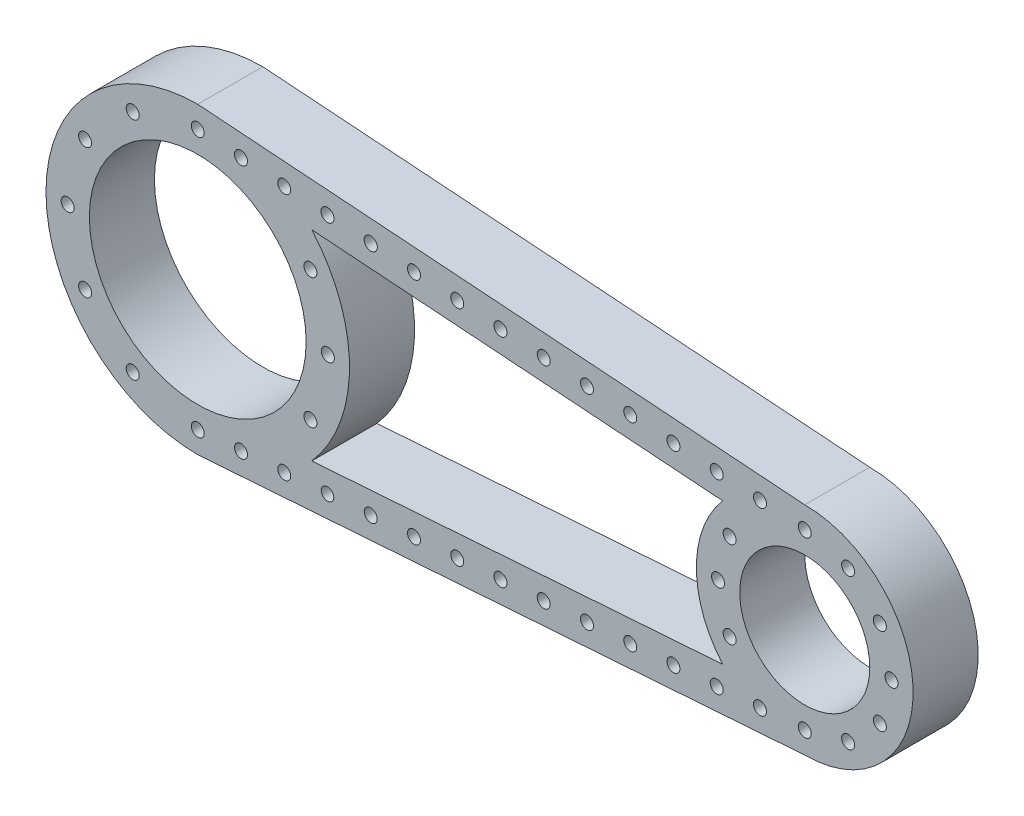
SolidWorks part; units mm, degrees
ref_plane "前视基准面" through (0, 0, 0) normal (0, 0, 1) x (1, 0, 0)
ref_plane "上视基准面" through (0, 0, 0) normal (0, 1, 0) x (1, 0, 0)
ref_plane "右视基准面" through (0, 0, 0) normal (1, 0, 0) x (0, 0, -1)
other "Configuration Table"
sketch "草图1" plane through (0, 0, 0) normal (0, 0, 1) x (1, 0, 0)
  line L0 (0, 0) -> (140, 0)
  line L1 (0, 35) -> (140, 25)
  line L2 (0, -35) -> (140, -25)
  circle A0 centre (0, 0) radius 35
  circle A1 centre (140, 0) radius 25
  dimension "D1" = 70
  dimension "D3" = 50
  dimension "D2" = 140
extrude "凸台-拉伸3" add sketch "草图1" along normal blind 5
sketch "草图4" plane through (0, 0, 5) normal (0, 0, 1) x (1, 0, 0)
  line L1 (-5, -5) -> (5, -5)
  line L2 (-5, -5) -> (-5, 5)
  line L3 (-5, 5) -> (5, 5)
  line L4 (5, -5) -> (5, 5)
  line L5 (-5, -5) -> (5, 5) construction
  line L6 (-5, 5) -> (5, -5) construction
  line L7 (135, -5) -> (145, -5)
  line L8 (135, -5) -> (135, 5)
  line L9 (135, 5) -> (145, 5)
  line L10 (145, -5) -> (145, 5)
  line L11 (135, -5) -> (145, 5) construction
  line L12 (135, 5) -> (145, -5) construction
  circle A0 centre (0, 0) radius 4
  circle A1 centre (-5, 5) radius 1.5
  circle A2 centre (5, 5) radius 1.5
  circle A3 centre (5, -5) radius 1.5
  circle A4 centre (-5, -5) radius 1.5
  circle A5 centre (140, 0) radius 4
  circle A6 centre (135, 5) radius 1.5
  circle A7 centre (145, 5) radius 1.5
  circle A8 centre (145, -5) radius 1.5
  circle A9 centre (135, -5) radius 1.5
  dimension "D1" = 8
  dimension "D4" = 3
  dimension "D6" = 8
  dimension "D9" = 3
  dimension "D2" = 10
  dimension "D3" = 10
  dimension "D7" = 10
  dimension "D8" = 10
  dimension "D5" = 4
  dimension "D10" = 4
extrude "切除-拉伸3" cut sketch "草图4" against normal blind 5 contours A5 | A0 | L2 A4 L1 | L1 A4 L2 | A6 | A9 | A8 | A7 | A1 | A2 | A3
sketch "草图5" plane through (0, 0, 5) normal (0, 0, 1) x (1, 0, 0)
  circle A0 centre (0, 0) radius 11
  circle A1 centre (140, 0) radius 11
  dimension "D1" = 22
  dimension "D2" = 22
extrude "切除-拉伸4" cut sketch "草图5" against normal blind 2
sketch "草图6" plane through (0, 0, 5) normal (0, 0, 1) x (1, 0, 0)
  circle A0 centre (0, 0) radius 30
  circle A1 centre (0, 30) radius 1.5
  circle A2 centre (15, 25.9808) radius 1.5
  circle A3 centre (25.9808, 15) radius 1.5
  circle A4 centre (30, 0) radius 1.5
  circle A5 centre (25.9808, -15) radius 1.5
  circle A6 centre (15, -25.9808) radius 1.5
  circle A7 centre (0, -30) radius 1.5
  circle A8 centre (-15, -25.9808) radius 1.5
  circle A9 centre (-25.9808, -15) radius 1.5
  circle A10 centre (-30, 0) radius 1.5
  circle A11 centre (-25.9808, 15) radius 1.5
  circle A12 centre (-15, 25.9808) radius 1.5
  circle A13 centre (140, 0) radius 20
  circle A14 centre (140, 20) radius 1.5
  circle A15 centre (150, 17.3205) radius 1.5
  circle A16 centre (157.3205, 10) radius 1.5
  circle A17 centre (160, 0) radius 1.5
  circle A18 centre (157.3205, -10) radius 1.5
  circle A19 centre (150, -17.3205) radius 1.5
  circle A20 centre (140, -20) radius 1.5
  circle A21 centre (130, -17.3205) radius 1.5
  circle A22 centre (122.6795, -10) radius 1.5
  circle A23 centre (120, 0) radius 1.5
  circle A24 centre (122.6795, 10) radius 1.5
  circle A25 centre (130, 17.3205) radius 1.5
  point P29 (0, 0)
  dimension "D1" = 60
  dimension "D2" = 3
  dimension "D4" = 40
  dimension "D5" = 3
  dimension "D3" = 12
  dimension "D6" = 12
extrude "切除-拉伸6" cut sketch "草图6" against normal through all contours A0 A12 | A11 | A1 | A2 | A3 | A4 | A5 | A6 | A7 | A8 | A9 | A10 | A25 | A14 | A15 | A16 | A17 | A18 | A19 | A20 | A21 | A22 | A23 | A24
sketch "草图8" plane through (0, 0, 5) normal (0, 0, 1) x (1, 0, 0)
  line L4 (-0.1715, -29.9995) -> (139.8316, -19.9993)
  line L5 (139.8316, 19.9993) -> (-0.1715, 29.9995)
  line L6 (-0.1715, -29.9995) -> (139.8316, -19.9993)
  line L7 (139.8316, 19.9993) -> (-0.1715, 29.9995)
  line L8 (-0.7125, 25.0254) -> (139.2875, 15.0254)
  line L9 (-0.7125, 25.0254) -> (139.2875, 15.0254)
  line L11 (-0.7125, -25.0254) -> (139.2875, -15.0254)
  line L12 (-0.7125, -25.0254) -> (139.2875, -15.0254)
  circle A3 centre (0, 30) radius 1.5
  arc A4 (139.8316, -19.9993) -> (139.8316, 19.9993) centre (140, 0) ccw
  arc A5 (-0.1715, 29.9995) -> (-0.1715, -29.9995) centre (0, 0) ccw
  arc A6 (139.8316, -19.9993) -> (139.8316, 19.9993) centre (140, 0) ccw
  arc A7 (-0.1715, 29.9995) -> (-0.1715, -29.9995) centre (0, 0) ccw
  circle A8 centre (9.9746, 29.2875) radius 1.5
  circle A9 centre (19.9492, 28.5751) radius 1.5
  circle A10 centre (29.9238, 27.8626) radius 1.5
  circle A11 centre (39.8983, 27.1501) radius 1.5
  circle A12 centre (49.8729, 26.4376) radius 1.5
  circle A13 centre (59.8475, 25.7252) radius 1.5
  circle A14 centre (69.8221, 25.0127) radius 1.5
  circle A15 centre (79.7967, 24.3002) radius 1.5
  circle A16 centre (89.7713, 23.5878) radius 1.5
  circle A17 centre (99.7459, 22.8753) radius 1.5
  circle A18 centre (109.7205, 22.1628) radius 1.5
  circle A19 centre (119.695, 21.4504) radius 1.5
  circle A20 centre (129.6696, 20.7379) radius 1.5
  circle A21 centre (0, -30) radius 1.5
  circle A22 centre (9.9746, -29.2875) radius 1.5
  circle A23 centre (19.9492, -28.5751) radius 1.5
  circle A24 centre (29.9238, -27.8626) radius 1.5
  circle A25 centre (39.8983, -27.1501) radius 1.5
  circle A26 centre (49.8729, -26.4376) radius 1.5
  circle A27 centre (59.8475, -25.7252) radius 1.5
  circle A28 centre (69.8221, -25.0127) radius 1.5
  circle A29 centre (79.7967, -24.3002) radius 1.5
  circle A30 centre (89.7713, -23.5878) radius 1.5
  circle A31 centre (99.7459, -22.8753) radius 1.5
  circle A32 centre (109.7205, -22.1628) radius 1.5
  circle A33 centre (119.695, -21.4504) radius 1.5
  circle A34 centre (129.6696, -20.7379) radius 1.5
  circle A35 centre (0, 0) radius 35
  circle A36 centre (140, 0) radius 25
  dimension "D2" = 14
  dimension "D1" = 5
  dimension "D4" = 10
  dimension "D5" = 10
  dimension "D3" = 14
extrude "切除-拉伸8" cut sketch "草图8" against normal through all contours A36 L9 A35 L12 | L6 A25 | L6 A25 | A8 | A9 | A10 | A11 | A12 | A13 | A14 | A16 | A15 | A17 | A18 | A19 | A20 | A34 | A33 | A32 | A31 | A30 | A29 | A28 | A27 | A26 | A24 | A23 | A22
sketch "草图10" plane through (0, 0, 5) normal (0, 0, 1) x (1, 0, 0)
  circle A0 centre (0, 0) radius 25
  circle A1 centre (140, 0) radius 15
  dimension "D1" = 50
  dimension "D2" = 30
extrude "切除-拉伸9" cut sketch "草图10" against normal through all
sketch "草图11" plane through (0, 0, 5) normal (0, 0, 1) x (1, 0, 0)
  line L0 (140, 25) -> (0, 35)
  line L1 (26.2977, 23.0961) -> (121.0676, 16.3268)
  line L2 (26.2977, -23.0961) -> (121.0676, -16.3268)
  line L3 (0, -35) -> (140, -25)
  circle A0 centre (0, 0) radius 25
  circle A1 centre (0, 0) radius 35
  circle A2 centre (140, 0) radius 15
  circle A3 centre (140, 0) radius 25
extrude "凸台-拉伸4" add sketch "草图11" along normal blind 10 contours A3 A2 | A3 L0 A1 L1 | A3 L2 A1 L3 | A1 L0 L3 A0
sketch "草图13" plane through (0, 0, 0) normal (0, 0, -1) x (-1, 0, 0)
  circle A0 centre (-150, 17.3205) radius 1.5
  circle A1 centre (-157.3205, 10) radius 1.5
  circle A2 centre (-160, 0) radius 1.5
  circle A3 centre (-157.3205, -10) radius 1.5
  circle A4 centre (-150, -17.3205) radius 1.5
  circle A5 centre (-140, -20) radius 1.5
  circle A6 centre (-120, 0) radius 1.5
  circle A7 centre (-122.6795, 10) radius 1.5
  circle A8 centre (-122.6795, -10) radius 1.5
  circle A9 centre (-129.6696, -20.7379) radius 1.5
  circle A10 centre (-119.695, -21.4504) radius 1.5
  circle A11 centre (-109.7205, -22.1628) radius 1.5
  circle A12 centre (-99.7459, -22.8753) radius 1.5
  circle A13 centre (-140, 20) radius 1.5
  circle A14 centre (-129.6696, 20.7379) radius 1.5
  circle A15 centre (-119.695, 21.4504) radius 1.5
  circle A16 centre (-109.7205, 22.1628) radius 1.5
  circle A17 centre (-99.7459, 22.8753) radius 1.5
  circle A18 centre (-89.7713, 23.5878) radius 1.5
  circle A19 centre (-79.7967, 24.3002) radius 1.5
  circle A20 centre (-69.8221, 25.0127) radius 1.5
  circle A21 centre (-59.8475, 25.7252) radius 1.5
  circle A22 centre (-49.8729, 26.4376) radius 1.5
  circle A23 centre (-39.8983, 27.1501) radius 1.5224
  circle A24 centre (-29.9238, 27.8626) radius 1.5
  circle A25 centre (-19.9492, 28.5751) radius 1.5
  circle A26 centre (-9.9746, 29.2875) radius 1.5
  circle A27 centre (0, 30) radius 1.5
  circle A28 centre (15, 25.9808) radius 1.5
  circle A29 centre (25.9808, 15) radius 1.5
  circle A30 centre (30, 0) radius 1.5
  circle A31 centre (25.9808, -15) radius 1.5
  circle A32 centre (15, -25.9808) radius 1.5
  circle A33 centre (0, -30) radius 1.5
  circle A34 centre (-9.9746, -29.2875) radius 1.5
  circle A35 centre (-19.9492, -28.5751) radius 1.5
  circle A36 centre (-29.9238, -27.8626) radius 1.4462
  circle A37 centre (-39.8983, -27.1501) radius 1.5
  circle A38 centre (-49.8729, -26.4376) radius 1.5
  circle A39 centre (-59.8475, -25.7252) radius 1.5
  circle A40 centre (-69.8221, -25.0127) radius 1.5
  circle A41 centre (-79.7967, -24.3002) radius 1.5
  circle A42 centre (-89.7713, -23.5878) radius 1.5
  circle A43 centre (-30, 0) radius 1.5
  circle A44 centre (-25.9808, -15) radius 1.5
  circle A45 centre (-25.9808, 15) radius 1.5
extrude "切除-拉伸10" cut sketch "草图13" against normal through all
